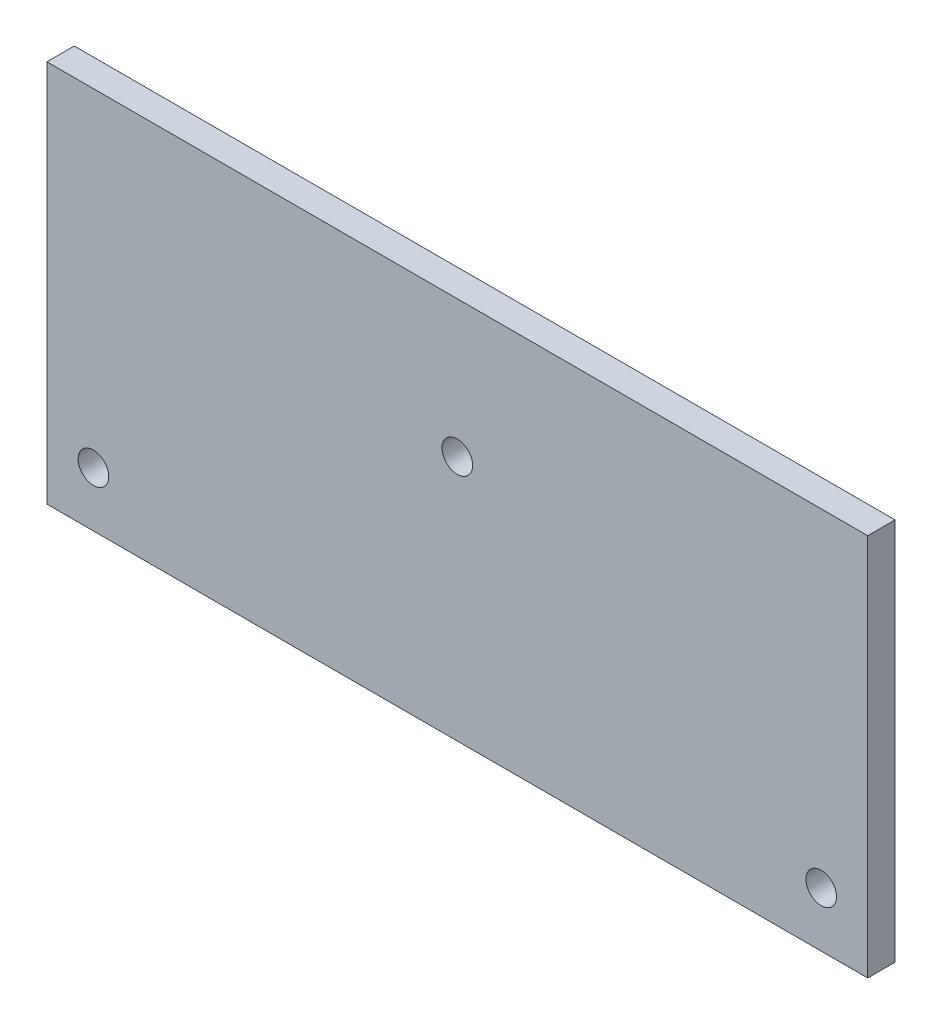
SolidWorks part; units mm, degrees
ref_plane "Plan de face" through (0, 0, 0) normal (0, 0, 1) x (1, 0, 0)
ref_plane "Plan de dessus" through (0, 0, 0) normal (0, 1, 0) x (1, 0, 0)
ref_plane "Plan de droite" through (0, 0, 0) normal (1, 0, 0) x (0, 0, -1)
sketch "Esquisse1" plane through (0, 0, 0) normal (0, 0, 1) x (1, 0, 0)
  line L0 (8.5, -60) -> (141.5, -60) construction
  line L1 (0, 0) -> (150, 0)
  line L2 (0, 0) -> (0, -70)
  line L3 (0, -70) -> (150, -70)
  line L4 (150, 0) -> (150, -70)
  circle A0 centre (75, -25) radius 2.8
  circle A1 centre (8.5, -60) radius 2.8
  circle A2 centre (141.5, -60) radius 2.8
  dimension "D3" = 5.6
  dimension "D4" = 75
  dimension "D6" = 5.6
  dimension "D1" = 150
  dimension "D2" = 70
  dimension "D5" = 25
  dimension "D7" = 8.5
  dimension "D8" = 10
  dimension "D9" = 8.5
extrude "Boss.-Extru.1" add sketch "Esquisse1" along normal blind 5
